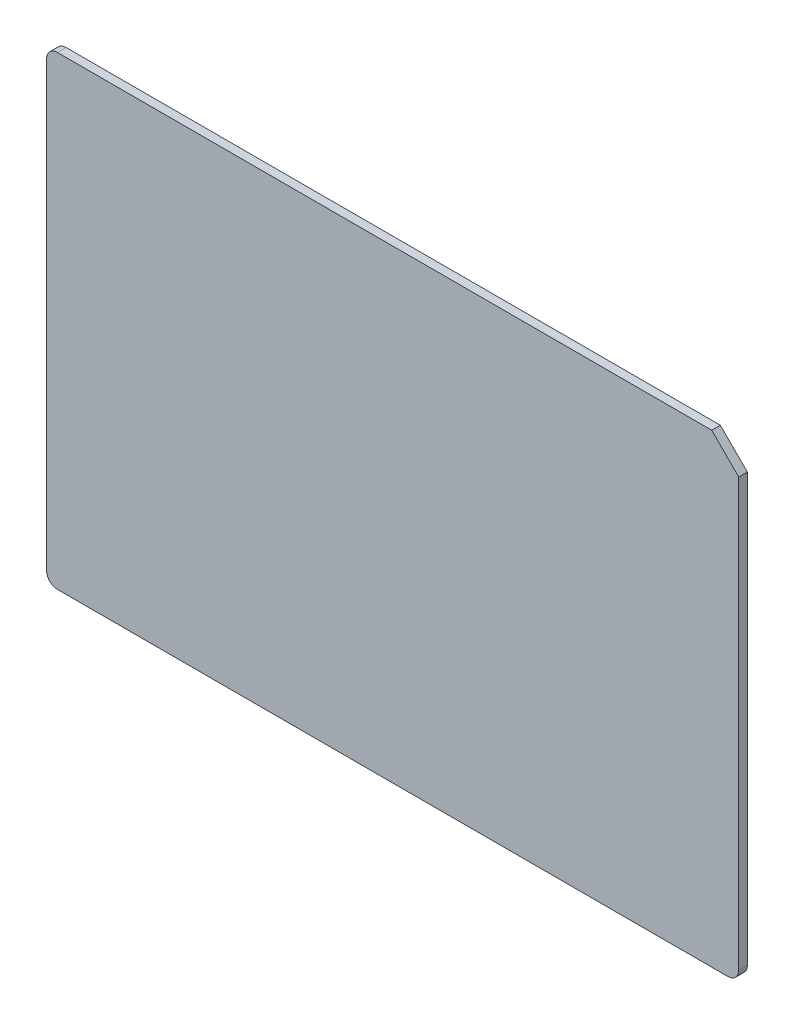
SolidWorks part; units mm, degrees
ref_plane "Front Plane" through (0, 0, 0) normal (0, 0, 1) x (1, 0, 0)
ref_plane "Top Plane" through (0, 0, 0) normal (0, 1, 0) x (1, 0, 0)
ref_plane "Right Plane" through (0, 0, 0) normal (1, 0, 0) x (0, 0, -1)
sketch "Sketch1" plane through (0, 0, 0) normal (0, 0, 1) x (1, 0, 0)
  line L5 (-2.2463, 79.8982) -> (-2.2463, -2.1018)
  line L6 (-0.2463, -4.1018) -> (123.7537, -4.1018)
  line L7 (125.7537, -2.1018) -> (125.7537, 76.8982)
  line L8 (125.7537, 76.8982) -> (120.7537, 81.8982)
  line L9 (120.7537, 81.8982) -> (-0.2463, 81.8982)
  arc A6 (-0.2463, 81.8982) -> (-2.2463, 79.8982) centre (-0.2463, 79.8982) ccw
  arc A7 (-2.2463, -2.1018) -> (-0.2463, -4.1018) centre (-0.2463, -2.1018) ccw
  arc A8 (123.7537, -4.1018) -> (125.7537, -2.1018) centre (123.7537, -2.1018) ccw
  point P0 (0, 0)
extrude "Boss-Extrude1" add sketch "Sketch1" along normal blind 1.6
